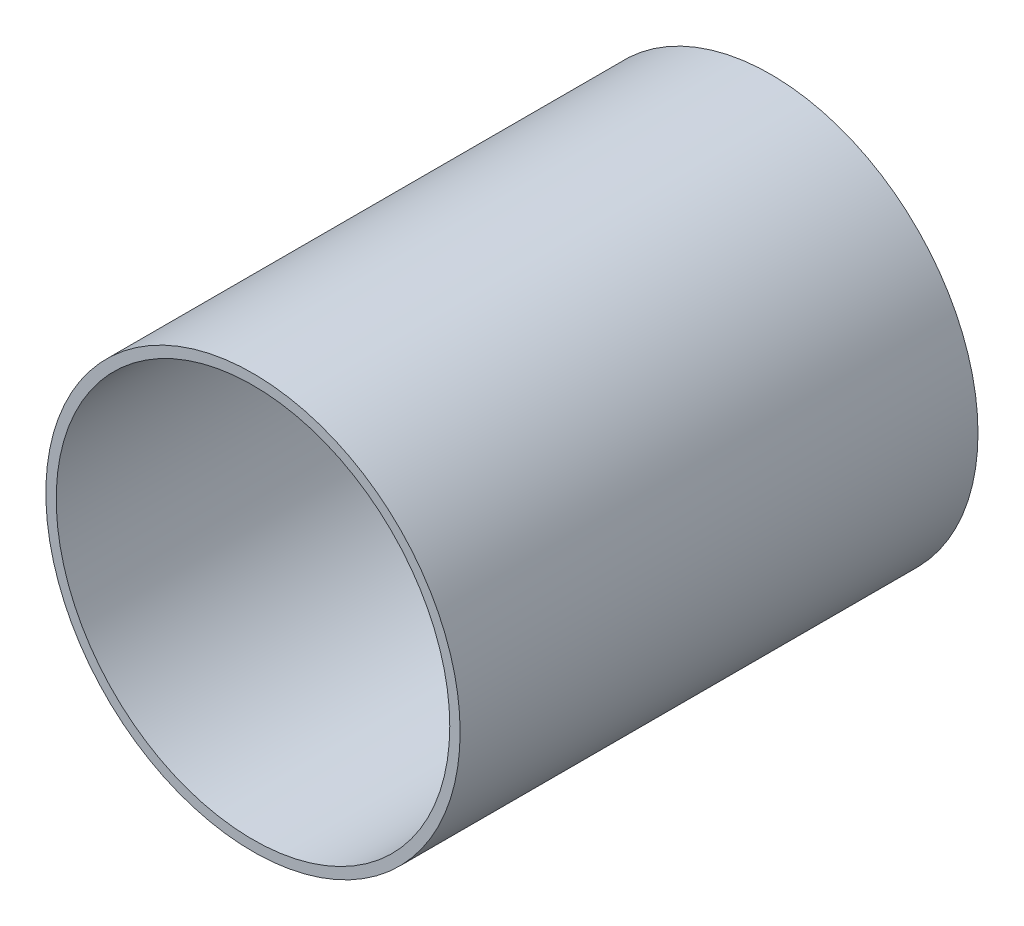
SolidWorks part; units mm, degrees
ref_plane "Front Plane" through (0, 0, 0) normal (0, 0, 1) x (1, 0, 0)
ref_plane "Top Plane" through (0, 0, 0) normal (0, 1, 0) x (1, 0, 0)
ref_plane "Right Plane" through (0, 0, 0) normal (1, 0, 0) x (0, 0, -1)
sketch "Sketch1" plane through (0, 0, 0) normal (0, 0, 1) x (1, 0, 0)
  circle A0 centre (0, 0) radius 40
  dimension "D1" = 80
extrude "Boss-Extrude1" add sketch "Sketch1" along normal mid plane 2
sketch "Sketch2" plane through (0, 0, 1) normal (0, 0, 1) x (1, 0, 0)
  circle A0 centre (0, 0) radius 40
  circle A1 centre (0, 0) radius 38
  circle A2 centre (0, 0) radius 40 construction
  dimension "D1" = 2
  dimension "D2" = 0
extrude "Boss-Extrude2" add sketch "Sketch2" along normal blind 98
